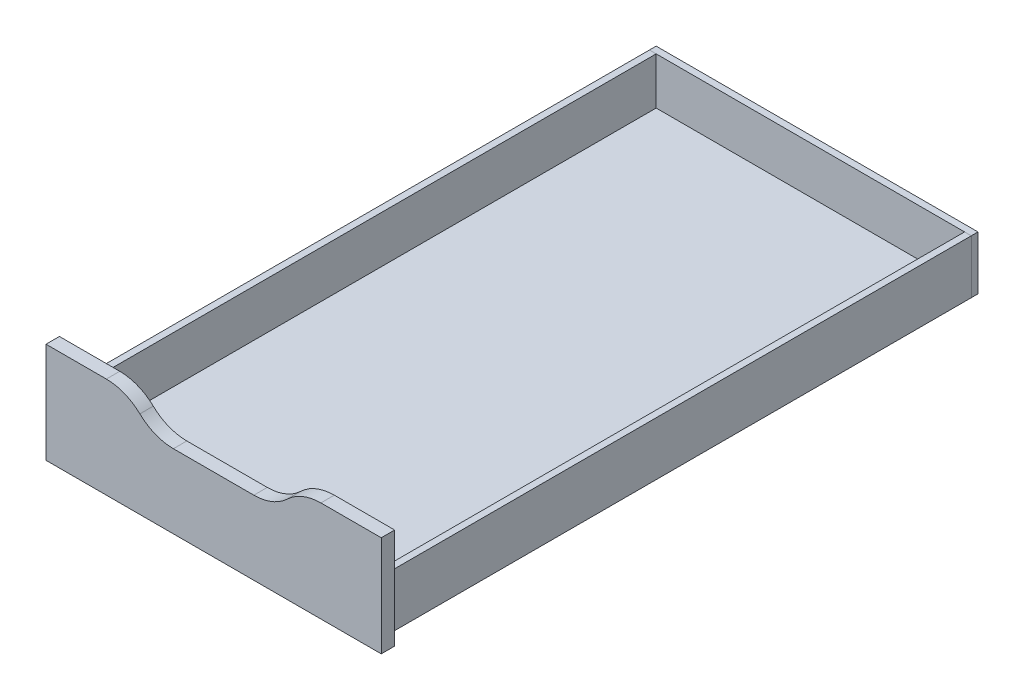
SolidWorks part; units mm, degrees
other "Bottom panel"
other "Front panel"
other "Right panel"
other "Left panel"
other "Back panel"
material "Beech"
ref_plane "Front Plane" through (0, 0, 0) normal (0, 0, 1) x (1, 0, 0)
ref_plane "Top Plane" through (0, 0, 0) normal (0, 1, 0) x (1, 0, 0)
ref_plane "Right Plane" through (0, 0, 0) normal (1, 0, 0) x (0, 0, -1)
sketch "Sketch1" plane through (0, 0, 0) normal (0, 1, 0) x (1, 0, 0)
  line L0 (-146.05, 273.05) -> (146.05, 273.05)
  line L1 (-146.05, -279.4) -> (146.05, -279.4)
  line L2 (-146.05, -279.4) -> (-146.05, 273.05)
  line L3 (-146.05, 279.4) -> (146.05, 279.4) construction
  line L4 (146.05, -279.4) -> (146.05, 273.05)
  line L5 (-146.05, -279.4) -> (146.05, 279.4) construction
  line L6 (-146.05, 279.4) -> (146.05, -279.4) construction
  line L7 (-146.05, 273.05) -> (-146.05, 279.4) construction
  line L8 (146.05, 273.05) -> (146.05, 279.4) construction
  point P0 (0, 0)
  dimension "D1" = 292.1
  dimension "D2" = 558.8
  dimension "D3" = 6.35
extrude "Boss-Extrude1" add sketch "Sketch1" along normal blind 6.35
sketch "Sketch2" plane through (0, 0, 279.4) normal (0, 0, 1) x (1, 0, 0)
  line L0 (-146.05, 0) -> (146.05, 0) construction
  line L1 (-158.75, -6.35) -> (158.75, -6.35)
  line L2 (-158.75, -6.35) -> (-158.75, 88.9)
  line L3 (-158.75, 88.9) -> (158.75, 88.9)
  line L4 (158.75, -6.35) -> (158.75, 88.9)
  point P4 (0, -6.35)
  dimension "D1" = 317.5
  dimension "D2" = 95.25
  dimension "D3" = 6.35
extrude "Boss-Extrude2" add sketch "Sketch2" along normal blind 12.7 separate body
sketch "Sketch3" plane through (0, 0, 292.1) normal (0, 0, 1) x (1, 0, 0)
  line L0 (-101.6, 101.6) -> (101.6, 101.6)
  line L1 (101.6, 101.6) -> (101.6, 88.9)
  line L2 (158.75, 88.9) -> (-158.75, 88.9) construction
  line L3 (38.1, 63.5) -> (-38.1, 63.5)
  line L4 (-101.6, 88.9) -> (-101.6, 101.6)
  arc A0 (101.6, 88.9) -> (69.85, 76.2) centre (101.6, 42.8625) ccw
  arc A1 (69.85, 76.2) -> (38.1, 63.5) centre (38.1, 109.5375) cw
  arc A2 (-38.1, 63.5) -> (-69.85, 76.2) centre (-38.1, 109.5375) cw
  arc A3 (-69.85, 76.2) -> (-101.6, 88.9) centre (-101.6, 42.8625) ccw
  point P15 (0, 101.6)
  point P17 (0, 63.5)
  dimension "D1" = 203.2
  dimension "D2" = 25.4
  dimension "D3" = 12.7
  dimension "D4" = 76.2
extrude "Cut-Extrude1" cut sketch "Sketch3" against normal through all
sketch "Sketch4" plane through (146.05, 0, 0) normal (1, 0, 0) x (0, 0, -1)
  line L0 (-279.4, 6.35) -> (-279.4, 0) construction
  line L1 (-279.4, 0) -> (273.05, 0)
  line L2 (-279.4, 0) -> (-279.4, 50.8)
  line L3 (-279.4, 50.8) -> (273.05, 50.8)
  line L4 (273.05, 0) -> (273.05, 50.8)
  line L5 (-279.4, 0) -> (273.05, 0) construction
  line L6 (273.05, 6.35) -> (273.05, 0) construction
  line L8 (-292.1, 88.9) -> (-279.4, 88.9) construction
  dimension "D1" = 38.1
extrude "Boss-Extrude3" add sketch "Sketch4" along normal blind 6.35 separate body
mirror "Mirror2" about plane through (0, 0, 0) normal (1, 0, 0) of bodies 104
sketch "Sketch5" plane through (0, 0, -273.05) normal (0, 0, -1) x (-1, 0, 0)
  line L0 (-146.05, 0) -> (146.05, 0) construction
  line L1 (-152.4, 0) -> (152.4, 0)
  line L2 (-152.4, 0) -> (-152.4, 50.8)
  line L3 (-152.4, 50.8) -> (152.4, 50.8)
  line L4 (152.4, 0) -> (152.4, 50.8)
  line L5 (-152.4, 0) -> (-152.4, 50.8) construction
  line L6 (-152.4, 50.8) -> (-146.05, 50.8) construction
  line L7 (152.4, 0) -> (152.4, 50.8) construction
extrude "Boss-Extrude4" add sketch "Sketch5" along normal blind 6.35 separate body
